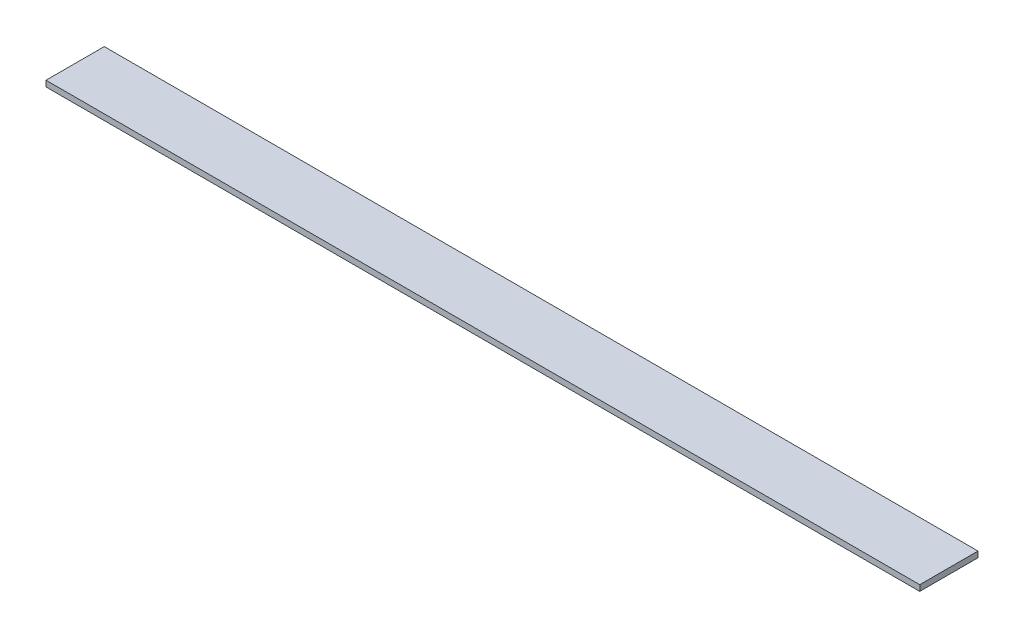
SolidWorks part; units mm, degrees
ref_plane "Front Plane" through (0, 0, 0) normal (0, 0, 1) x (1, 0, 0)
ref_plane "Top Plane" through (0, 0, 0) normal (0, 1, 0) x (1, 0, 0)
ref_plane "Right Plane" through (0, 0, 0) normal (1, 0, 0) x (0, 0, -1)
sketch "Sketch1" plane through (0, 0, 0) normal (1, 0, 0) x (0, 0, -1)
  line L0 (0, 0) -> (25.4, 0)
  line L1 (0, 0) -> (0, 2.54)
  line L2 (25.4, 0) -> (25.4, 2.54)
  line L3 (0, 2.54) -> (25.4, 2.54)
  dimension "D1" = 25.4
  dimension "D2" = 2.54
extrude "Boss-Extrude1" add sketch "Sketch1" along normal blind 381
